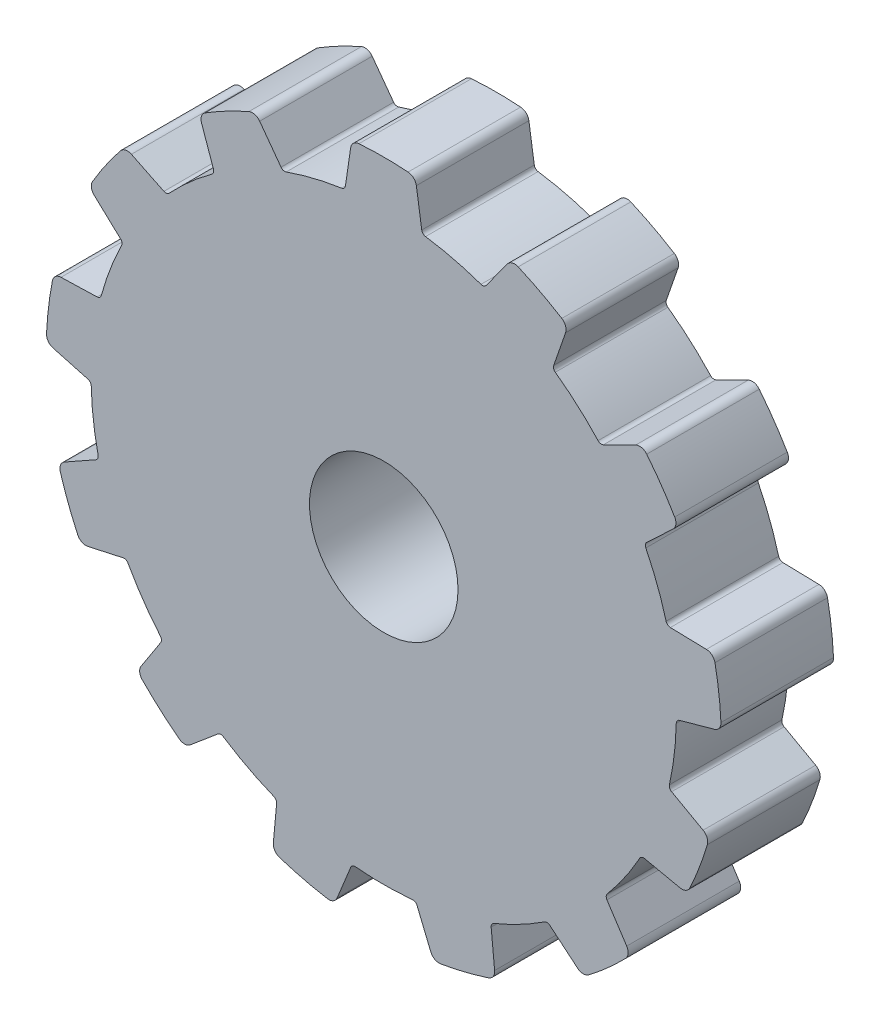
SolidWorks part; units mm, degrees
ref_plane "Plano frontal" through (0, 0, 0) normal (0, 0, 1) x (1, 0, 0)
ref_plane "Plano superior" through (0, 0, 0) normal (0, 1, 0) x (1, 0, 0)
ref_plane "Plano direito" through (0, 0, 0) normal (1, 0, 0) x (0, 0, -1)
sketch "Esboço1" plane through (0, 0, 0) normal (0, 0, 1) x (1, 0, 0)
  line L0 (0, 6) -> (0, 7.5) construction
  line L1 (2.2746, 6.1659) -> (2.7457, 6.8137)
  line L2 (4.039, 6.1367) -> (3.7764, 5.3784)
  line L3 (4.8795, 4.4026) -> (5.5977, 4.7572)
  line L4 (6.4283, 3.5567) -> (5.8433, 3.0074)
  line L5 (6.3666, 1.6307) -> (7.1673, 1.6109)
  line L6 (7.3449, 0.162) -> (6.5716, -0.0526)
  line L7 (6.3951, -1.5148) -> (7.0949, -1.9044)
  line L8 (6.5788, -3.2699) -> (5.7944, -3.1005)
  line L9 (-0.8514, 6.5167) -> (-0.7352, 7.3092)
  line L10 (0.7245, 7.3108) -> (0.8443, 6.5173)
  line L11 (4.9587, -4.3133) -> (5.3972, -4.9835)
  line L12 (4.3057, -5.9527) -> (3.6898, -5.4382)
  line L13 (2.3862, -6.1236) -> (2.4631, -6.9209)
  line L14 (1.0461, -7.2718) -> (0.7399, -6.53)
  line L15 (-0.7329, -6.5311) -> (-1.0353, -7.2728)
  line L16 (-2.4531, -6.925) -> (-2.3795, -6.1259)
  line L17 (-3.6841, -5.4424) -> (-4.2966, -5.9586)
  line L18 (-5.3903, -4.9918) -> (-4.9538, -4.3184)
  line L19 (-5.7913, -3.1069) -> (-6.5735, -3.2793)
  line L20 (-7.0927, -1.915) -> (-6.3932, -1.5216)
  line L21 (-6.5718, -0.0597) -> (-7.3445, 0.1512)
  line L22 (-7.1702, 1.6005) -> (-6.368, 1.6238)
  line L23 (-5.8468, 3.0012) -> (-6.433, 3.547)
  line L24 (-5.6051, 4.7493) -> (-4.884, 4.3971)
  line L25 (-3.7823, 5.3746) -> (-4.0478, 6.1303)
  line L26 (-2.756, 6.8101) -> (-2.2811, 6.1632)
  arc A0 (0.5412, 7.4804) -> (-0.5521, 7.4797) centre (0, 0) ccw
  arc A1 (-0.9359, 6.4323) -> (-2.1672, 6.1281) centre (0, 0) ccw
  arc A2 (0.5412, 7.4804) -> (0.7245, 7.3108) centre (0.5268, 7.281) cw
  arc A3 (-0.5521, 7.4797) -> (-0.7352, 7.3092) centre (-0.5373, 7.2802) ccw
  arc A4 (0.9289, 6.4333) -> (0.8443, 6.5173) centre (0.9432, 6.5323) cw
  arc A5 (-0.9359, 6.4323) -> (-0.8514, 6.5167) centre (-0.9503, 6.5312) ccw
  arc A6 (2.1605, 6.1304) -> (2.2746, 6.1659) centre (2.1937, 6.2248) ccw
  arc A7 (3.9555, 6.3721) -> (2.9871, 6.8795) centre (0, 0) ccw
  arc A8 (2.9871, 6.8795) -> (2.7457, 6.8137) centre (2.9075, 6.696) ccw
  arc A9 (3.9555, 6.3721) -> (4.039, 6.1367) centre (3.8501, 6.2022) cw
  arc A10 (3.8122, 5.2647) -> (3.7764, 5.3784) centre (3.8709, 5.3457) cw
  arc A11 (4.762, 4.4242) -> (4.8795, 4.4026) centre (4.8352, 4.4923) ccw
  arc A12 (6.4637, 3.804) -> (5.842, 4.7033) centre (0, 0) ccw
  arc A13 (5.842, 4.7033) -> (5.5977, 4.7572) centre (5.6862, 4.5778) ccw
  arc A14 (6.4637, 3.804) -> (6.4283, 3.5567) centre (6.2914, 3.7025) cw
  arc A15 (5.8222, 2.89) -> (5.8433, 3.0074) centre (5.9117, 2.9345) cw
  arc A16 (6.2726, 1.7044) -> (6.3666, 1.6307) centre (6.3691, 1.7307) ccw
  arc A17 (7.4911, 0.3644) -> (7.3586, 1.4496) centre (0, 0) ccw
  arc A18 (7.3586, 1.4496) -> (7.1673, 1.6109) centre (7.1623, 1.411) ccw
  arc A19 (7.4911, 0.3644) -> (7.3449, 0.162) centre (7.2914, 0.3547) cw
  arc A20 (6.4983, -0.1467) -> (6.5716, -0.0526) centre (6.5983, -0.149) cw
  arc A21 (6.3462, -1.4058) -> (6.3951, -1.5148) centre (6.4438, -1.4274) ccw
  arc A22 (6.8024, -3.1586) -> (7.1894, -2.1361) centre (0, 0) ccw
  arc A23 (7.1894, -2.1361) -> (7.0949, -1.9044) centre (6.9976, -2.0792) ccw
  arc A24 (6.8024, -3.1586) -> (6.5788, -3.2699) centre (6.621, -3.0744) cw
  arc A25 (5.6858, -3.1498) -> (5.7944, -3.1005) centre (5.7733, -3.1983) cw
  arc A26 (4.9659, -4.194) -> (4.9587, -4.3133) centre (5.0423, -4.2585) ccw
  arc A27 (4.5554, -5.9581) -> (5.3732, -5.2325) centre (0, 0) ccw
  arc A28 (5.3732, -5.2325) -> (5.3972, -4.9835) centre (5.2299, -5.093) ccw
  arc A29 (4.5554, -5.9581) -> (4.3057, -5.9527) centre (4.4339, -5.7992) cw
  arc A30 (3.5707, -5.4314) -> (3.6898, -5.4382) centre (3.6257, -5.5149) cw
  arc A31 (2.4481, -6.0214) -> (2.3862, -6.1236) centre (2.4857, -6.114) ccw
  arc A32 (1.2647, -7.3926) -> (2.326, -7.1302) centre (0, 0) ccw
  arc A33 (2.326, -7.1302) -> (2.4631, -6.9209) centre (2.264, -6.9401) ccw
  arc A34 (1.2647, -7.3926) -> (1.0461, -7.2718) centre (1.231, -7.1955) cw
  arc A35 (0.6377, -6.4686) -> (0.7399, -6.53) centre (0.6475, -6.5682) cw
  arc A36 (-0.6306, -6.4693) -> (-0.7329, -6.5311) centre (-0.6403, -6.5689) ccw
  arc A37 (-2.3157, -7.1336) -> (-1.254, -7.3944) centre (0, 0) ccw
  arc A38 (-1.254, -7.3944) -> (-1.0353, -7.2728) centre (-1.2205, -7.1972) ccw
  arc A39 (-2.3157, -7.1336) -> (-2.4531, -6.925) centre (-2.2539, -6.9433) cw
  arc A40 (-2.4415, -6.024) -> (-2.3795, -6.1259) centre (-2.4791, -6.1167) cw
  arc A41 (-3.5648, -5.4353) -> (-3.6841, -5.4424) centre (-3.6197, -5.5189) ccw
  arc A42 (-5.3655, -5.2403) -> (-4.5467, -5.9647) centre (0, 0) ccw
  arc A43 (-4.5467, -5.9647) -> (-4.2966, -5.9586) centre (-4.4255, -5.8056) ccw
  arc A44 (-5.3655, -5.2403) -> (-5.3903, -4.9918) centre (-5.2225, -5.1006) cw
  arc A45 (-4.9614, -4.1994) -> (-4.9538, -4.3184) centre (-5.0377, -4.264) cw
  arc A46 (-5.6824, -3.156) -> (-5.7913, -3.1069) centre (-5.7698, -3.2046) ccw
  arc A47 (-7.1863, -2.1466) -> (-6.7978, -3.1685) centre (0, 0) ccw
  arc A48 (-6.7978, -3.1685) -> (-6.5735, -3.2793) centre (-6.6166, -3.084) ccw
  arc A49 (-7.1863, -2.1466) -> (-7.0927, -1.915) centre (-6.9946, -2.0893) cw
  arc A50 (-6.3446, -1.4127) -> (-6.3932, -1.5216) centre (-6.4422, -1.4345) cw
  arc A51 (-6.4982, -0.1538) -> (-6.5718, -0.0597) centre (-6.5982, -0.1562) ccw
  arc A52 (-7.3607, 1.4389) -> (-7.4917, 0.3535) centre (0, 0) ccw
  arc A53 (-7.4917, 0.3535) -> (-7.3445, 0.1512) centre (-7.2919, 0.3441) ccw
  arc A54 (-7.3607, 1.4389) -> (-7.1702, 1.6005) centre (-7.1644, 1.4006) cw
  arc A55 (-6.2744, 1.6976) -> (-6.368, 1.6238) centre (-6.3709, 1.7237) cw
  arc A56 (-5.8253, 2.8837) -> (-5.8468, 3.0012) centre (-5.9149, 2.928) ccw
  arc A57 (-5.8489, 4.6948) -> (-6.4692, 3.7946) centre (0, 0) ccw
  arc A58 (-6.4692, 3.7946) -> (-6.433, 3.547) centre (-6.2967, 3.6934) ccw
  arc A59 (-5.8489, 4.6948) -> (-5.6051, 4.7493) centre (-5.6929, 4.5696) cw
  arc A60 (-4.7668, 4.419) -> (-4.884, 4.3971) centre (-4.8401, 4.487) cw
  arc A61 (-3.818, 5.2605) -> (-3.7823, 5.3746) centre (-3.8767, 5.3415) ccw
  arc A62 (-2.9971, 6.8751) -> (-3.9648, 6.3663) centre (0, 0) ccw
  arc A63 (-3.9648, 6.3663) -> (-4.0478, 6.1303) centre (-3.8591, 6.1966) ccw
  arc A64 (-2.9971, 6.8751) -> (-2.756, 6.8101) centre (-2.9172, 6.6918) cw
  arc A65 (-2.1672, 6.1281) -> (-2.2811, 6.1632) centre (-2.2005, 6.2224) cw
  arc A66 (-3.818, 5.2605) -> (-4.7668, 4.419) centre (0, 0) ccw
  arc A67 (-5.8253, 2.8837) -> (-6.2744, 1.6976) centre (0, 0) ccw
  arc A68 (-6.4982, -0.1538) -> (-6.3446, -1.4127) centre (0, 0) ccw
  arc A69 (-5.6824, -3.156) -> (-4.9614, -4.1994) centre (0, 0) ccw
  arc A70 (-0.6306, -6.4693) -> (0.6377, -6.4686) centre (0, 0) ccw
  arc A71 (2.4481, -6.0214) -> (3.5707, -5.4314) centre (0, 0) ccw
  arc A72 (4.9659, -4.194) -> (5.6858, -3.1498) centre (0, 0) ccw
  arc A73 (6.2726, 1.7044) -> (5.8222, 2.89) centre (0, 0) ccw
  arc A74 (4.762, 4.4242) -> (3.8122, 5.2647) centre (0, 0) ccw
  arc A75 (2.1605, 6.1304) -> (0.9289, 6.4333) centre (0, 0) ccw
  arc A76 (-3.5648, -5.4353) -> (-2.4415, -6.024) centre (0, 0) ccw
  arc A77 (6.3462, -1.4058) -> (6.4983, -0.1467) centre (0, 0) ccw
  point P17 (0, 0)
  point P18 (0, 0)
  point P162 (0, 0)
  dimension "D1" = 13
  dimension "D2" = 15
  dimension "D3" = 0.2
  dimension "D4" = 0.1
  dimension "D5" = 13
extrude "Ressalto-extrusão1" add sketch "Esboço1" along normal blind 2.5 contours A66 A60 L24 A59 A57 A58 L23 A56 A67 A55 L22 A54 A52 A53 L21 A51 A68 A50 L20 A49 A47 A48 L19 A46 A69 A45 L18 A44 A42 A43 L17 A41 A76 A40 L16 A39 A37 A38 L15 A36 A70 A35 L14 A34 A32 A33 L13 A31 A71 A30 L12 A29 A27 A28 L11 A26 A72 A25 L8 A24 A22 A23 L7 A21 A77 A20 L6 A19 A17 A18 L5 A16 A73 A15 L4 A14 A12 A13 L3 A11 A74 A10 L2 A9 A7 A8 L1 A6 A75 A4 L10 A2 A0 A3 L9 A5 A1 A65 L26 A64 A62 A63 L25 A61
sketch "Esboço2" plane through (0, 0, 2.5) normal (0, 0, 1) x (1, 0, 0)
  circle A0 centre (0, 0) radius 1.65
  dimension "D1" = 3.3
extrude "Corte-extrusão1" cut sketch "Esboço2" against normal through all
